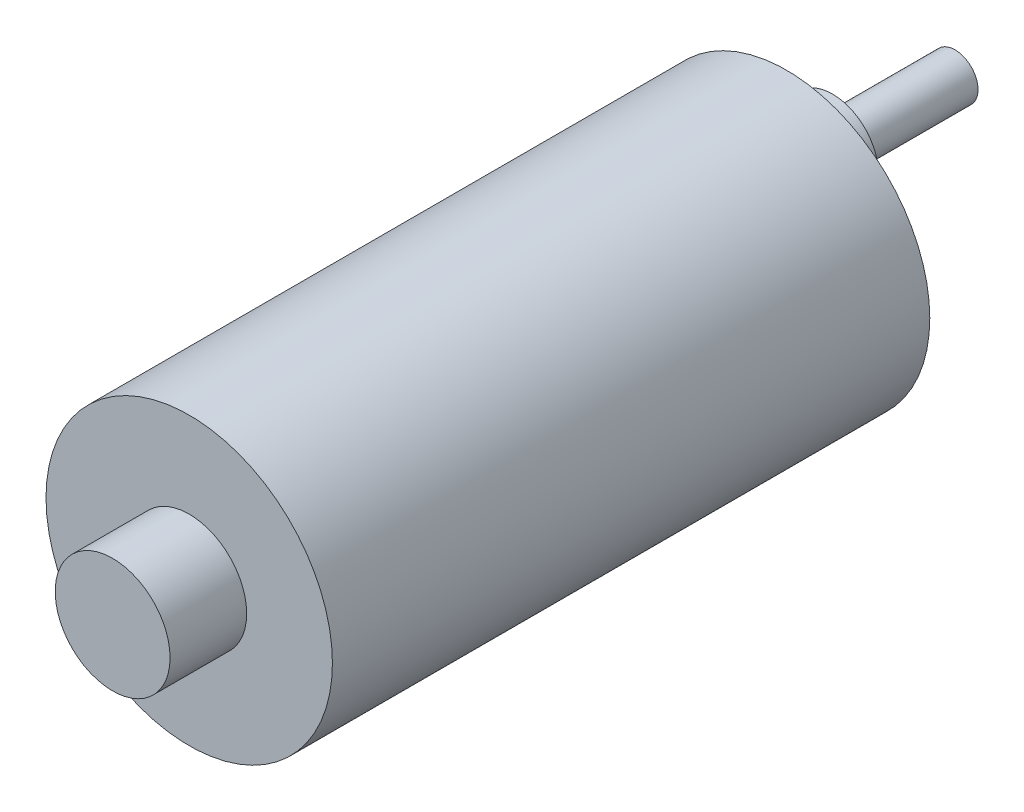
SolidWorks part; units mm, degrees
ref_plane "前视基准面" through (0, 0, 0) normal (0, 0, 1) x (1, 0, 0)
ref_plane "上视基准面" through (0, 0, 0) normal (0, 1, 0) x (1, 0, 0)
ref_plane "右视基准面" through (0, 0, 0) normal (1, 0, 0) x (0, 0, -1)
other "Configuration Table"
sketch "草图1" plane through (0, 0, 0) normal (0, 0, 1) x (1, 0, 0)
  circle A0 centre (0, 0) radius 18.7
  dimension "D1" = 37.4
extrude "凸台-拉伸1" add sketch "草图1" along normal blind 78
sketch "草图2" plane through (0, 0, 78) normal (0, 0, 1) x (1, 0, 0)
  circle A0 centre (0, 0) radius 7.5
  dimension "D1" = 15
extrude "凸台-拉伸2" add sketch "草图2" along normal blind 10
sketch "草图3" plane through (0, 0, 0) normal (0, 0, -1) x (-1, 0, 0)
  line L0 (0, 0) -> (0, 8.7651)
  circle A0 centre (0, 0) radius 15.5
  circle A1 centre (0, 15.5) radius 1.55
  circle A2 centre (13.4234, 7.75) radius 1.55
  circle A3 centre (13.4234, -7.75) radius 1.55
  circle A4 centre (0, -15.5) radius 1.55
  circle A5 centre (-13.4234, -7.75) radius 1.55
  circle A6 centre (-13.4234, 7.75) radius 1.55
  point P19 (0, 0)
  dimension "D2" = 31
  dimension "D3" = 3.1
  dimension "D1" = 8.7651
  dimension "D4" = 6
extrude "切除-拉伸1" cut sketch "草图3" against normal blind 10 and the other way through all contours A2 | A3 | A4 | A5 | A6 | A1
sketch "草图4" plane through (0, 0, 0) normal (0, 0, -1) x (-1, 0, 0)
  line L0 (0, 0) -> (0, 7)
  circle A0 centre (0, 7) radius 6
  dimension "D2" = 12
  dimension "D1" = 7
extrude "凸台-拉伸3" add sketch "草图4" along normal blind 6
sketch "草图5" plane through (0, 0, -6) normal (0, 0, -1) x (-1, 0, 0)
  circle A0 centre (0, 7) radius 3
  dimension "D1" = 6
extrude "凸台-拉伸4" add sketch "草图5" along normal blind 16
